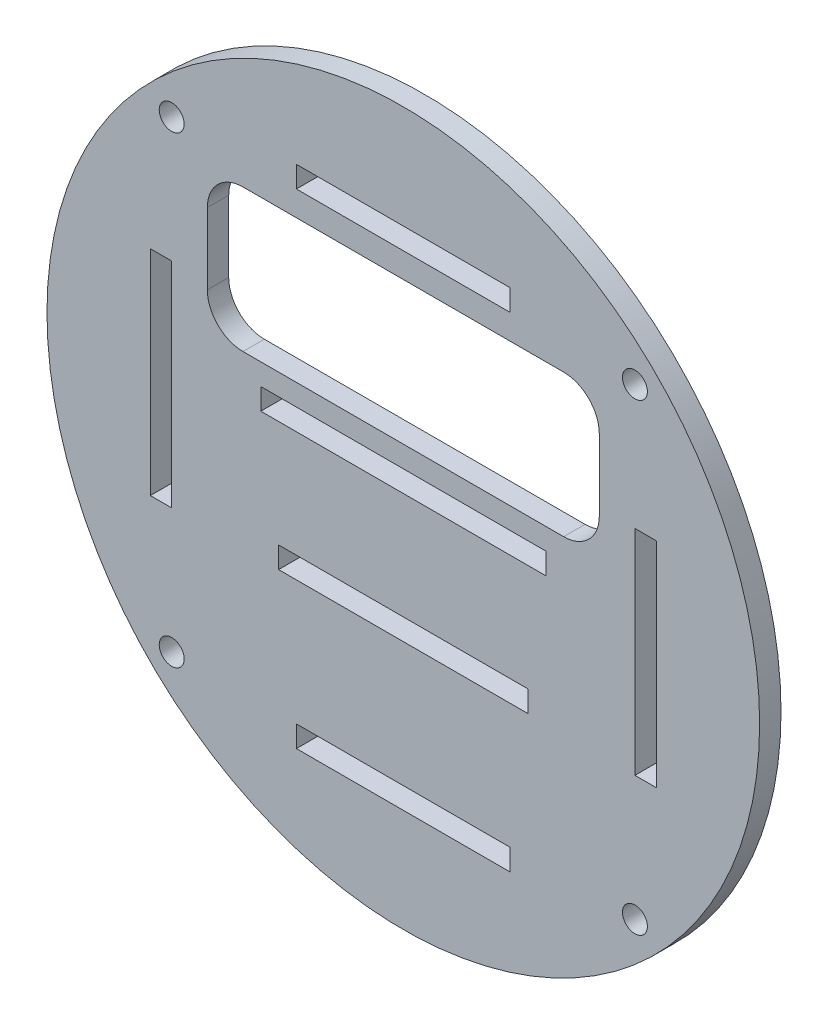
SolidWorks part; units mm, degrees
material "ABS"
ref_plane "Спереди" through (0, 0, 0) normal (0, 0, 1) x (1, 0, 0)
ref_plane "Сверху" through (0, 0, 0) normal (0, 1, 0) x (1, 0, 0)
ref_plane "Справа" through (0, 0, 0) normal (1, 0, 0) x (0, 0, -1)
sketch "Эскиз1" plane through (0, 0, 0) normal (0, 0, 1) x (1, 0, 0)
  circle A0 centre (0, 0) radius 50
  dimension "D1" = 100
extrude "Бобышка-Вытянуть1" add sketch "Эскиз1" along normal blind 3
sketch "Эскиз2" plane through (0, 0, 3) normal (0, 0, 1) x (1, 0, 0)
  line L0 (0, 50) -> (0, -50) construction
  line L1 (-50, 0) -> (50, 0) construction
  line L2 (-15, -32.5) -> (15, -32.5)
  line L3 (-15, -32.5) -> (-15, -35.5)
  line L4 (-15, -35.5) -> (15, -35.5)
  line L5 (15, -32.5) -> (15, -35.5)
  line L6 (-15, -32.5) -> (15, -35.5) construction
  line L7 (-15, -35.5) -> (15, -32.5) construction
  line L8 (-17.5, -12) -> (17.5, -12)
  line L9 (-17.5, -12) -> (-17.5, -15)
  line L10 (-17.5, -15) -> (17.5, -15)
  line L11 (17.5, -12) -> (17.5, -15)
  line L12 (-17.5, -12) -> (17.5, -15) construction
  line L13 (-17.5, -15) -> (17.5, -12) construction
  line L14 (-20, 6) -> (20, 6)
  line L15 (-20, 6) -> (-20, 3)
  line L16 (-20, 3) -> (20, 3)
  line L17 (20, 6) -> (20, 3)
  line L18 (-20, 6) -> (20, 3) construction
  line L19 (-20, 3) -> (20, 6) construction
  line L20 (-15, 35.5) -> (15, 32.5) construction
  line L21 (-15, 32.5) -> (15, 35.5) construction
  line L22 (15, 32.5) -> (15, 35.5)
  line L23 (-15, 35.5) -> (15, 35.5)
  line L24 (-15, 32.5) -> (-15, 35.5)
  line L25 (-15, 32.5) -> (15, 32.5)
  circle A0 centre (0, 0) radius 50 construction
  point P5 (0, -34)
  point P10 (0, -13.5)
  point P16 (0, 0)
  point P27 (0, 34)
  point P28 (0, 0)
  point P29 (0, 0)
  point P30 (0, 0)
  point P31 (0, 0)
  dimension "D1" = 3
  dimension "D2" = 30
  dimension "D3" = 32.5
  dimension "D4" = 3
  dimension "D5" = 35
  dimension "D6" = 17.5
  dimension "D7" = 3
  dimension "D8" = 40
  dimension "D9" = 15
extrude "Вырез-Вытянуть1" cut sketch "Эскиз2" against normal blind 8
sketch "Эскиз3" plane through (0, 0, 0) normal (0, 0, -1) x (-1, 0, 0)
  line L0 (-20, 6) -> (20, 6) construction
  line L1 (-22.5, 29) -> (22.5, 29)
  line L2 (-27.5, 24) -> (-27.5, 14)
  line L3 (-22.5, 9) -> (22.5, 9)
  line L4 (27.5, 24) -> (27.5, 14)
  line L5 (-27.5, 29) -> (27.5, 9) construction
  line L6 (-27.5, 9) -> (27.5, 29) construction
  line L7 (0, 0) -> (0, 36.6116) construction
  arc A0 (-27.5, 14) -> (-22.5, 9) centre (-22.5, 14) ccw
  arc A1 (22.5, 9) -> (27.5, 14) centre (22.5, 14) ccw
  arc A2 (22.5, 29) -> (27.5, 24) centre (22.5, 24) cw
  arc A3 (-22.5, 29) -> (-27.5, 24) centre (-22.5, 24) ccw
  point P0 (0, 19)
  dimension "D4" = 5
  dimension "D1" = 3
  dimension "D2" = 20
  dimension "D3" = 55
extrude "Вырез-Вытянуть2" cut sketch "Эскиз3" against normal blind 10
sketch "Эскиз4" plane through (0, 0, 0) normal (0, 0, -1) x (-1, 0, 0)
  line L0 (0, 50) -> (0, -50) construction
  line L1 (-50, 0) -> (50, 0) construction
  line L2 (32.5, -15) -> (35.4957, 15) construction
  line L3 (-32.5, 15) -> (-35.4957, 15)
  line L4 (-32.5, 15) -> (-32.5, -15)
  line L5 (-32.5, -15) -> (-35.4957, -15)
  line L6 (-35.4957, 15) -> (-35.4957, -15)
  line L7 (-32.5, 15) -> (-35.4957, -15) construction
  line L8 (-32.5, -15) -> (-35.4957, 15) construction
  line L9 (32.5, 15) -> (35.4957, -15) construction
  line L10 (35.4957, 15) -> (35.4957, -15)
  line L11 (32.5, -15) -> (35.4957, -15)
  line L12 (32.5, 15) -> (32.5, -15)
  line L13 (32.5, 15) -> (35.4957, 15)
  circle A0 centre (0, 0) radius 50 construction
  point P7 (-33.9978, 0)
  point P17 (33.9978, 0)
  dimension "D1" = 2.9957
  dimension "D2" = 30
  dimension "D3" = 32.5
extrude "Вырез-Вытянуть3" cut sketch "Эскиз4" against normal blind 10
sketch "Эскиз5" plane through (0, 0, 3) normal (0, 0, 1) x (1, 0, 0)
  line L1 (-32.5, -32.5) -> (32.5, -32.5) construction
  line L2 (-32.5, -32.5) -> (-32.5, 32.5) construction
  line L3 (-32.5, 32.5) -> (32.5, 32.5) construction
  line L4 (32.5, -32.5) -> (32.5, 32.5) construction
  line L5 (-32.5, -32.5) -> (32.5, 32.5) construction
  line L6 (-32.5, 32.5) -> (32.5, -32.5) construction
  circle A0 centre (-32.5, 32.5) radius 1.75
  circle A1 centre (32.5, 32.5) radius 1.75
  circle A2 centre (32.5, -32.5) radius 1.75
  circle A3 centre (-32.5, -32.5) radius 1.75
  point P0 (0, 0)
  dimension "D3" = 3.5
  dimension "D1" = 65
  dimension "D2" = 65
extrude "Вырез-Вытянуть4" cut sketch "Эскиз5" against normal blind 10
